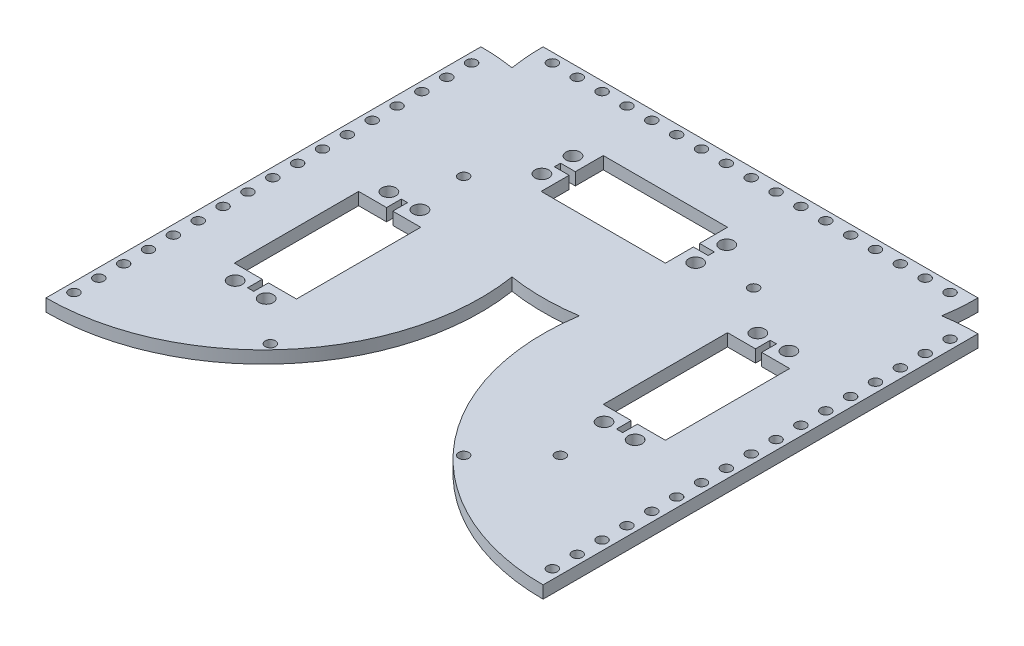
SolidWorks part; units mm, degrees
ref_plane "前视基准面" through (0, 0, 0) normal (0, 0, 1) x (1, 0, 0)
ref_plane "上视基准面" through (0, 0, 0) normal (0, 1, 0) x (1, 0, 0)
ref_plane "右视基准面" through (0, 0, 0) normal (1, 0, 0) x (0, 0, -1)
sketch "草图1" plane through (0, 0, 0) normal (0, 1, 0) x (1, 0, 0)
  line L0 (-50, 0) -> (50, 0)
  arc A0 (50, 0) -> (-50, 0) centre (0, 0) cw
extrude "凸台-拉伸1" add sketch "草图1" along normal blind 4
sketch "草图2" plane through (0, 4, 0) normal (0, 1, 0) x (1, 0, 0)
  line L2 (0, -10.623) -> (10, -10.623)
  line L3 (10, -10.623) -> (10, -30.623)
  line L4 (10, -30.623) -> (-30, -30.623)
  line L5 (-30, -30.623) -> (-30, -10.623)
  line L6 (-30, -10.623) -> (0, -10.623)
extrude "切除-拉伸1" cut sketch "草图2" against normal blind 10
sketch "草图3" plane through (0, 4, 0) normal (0, 1, 0) x (1, 0, 0)
  circle A0 centre (-34.75, -15.623) radius 2.25
  circle A1 centre (-34.75, -25.623) radius 2.25
  circle A2 centre (14.75, -25.623) radius 2.25
  circle A3 centre (14.75, -15.623) radius 2.25
extrude "切除-拉伸2" cut sketch "草图3" against normal blind 10
sketch "草图4" plane through (0, 4, 0) normal (0, 1, 0) x (1, 0, 0)
  circle A0 centre (0, -3) radius 1.65
  circle A1 centre (8, -3) radius 1.65
  circle A2 centre (16, -3) radius 1.65
  circle A3 centre (24, -3) radius 1.65
  circle A4 centre (32, -3) radius 1.65
  circle A5 centre (40, -3) radius 1.65
  circle A6 centre (-40, -3) radius 1.65
  circle A7 centre (-32, -3) radius 1.65
  circle A8 centre (-24, -3) radius 1.65
  circle A9 centre (-16, -3) radius 1.65
  circle A10 centre (-8, -3) radius 1.65
extrude "切除-拉伸3" cut sketch "草图4" against normal blind 10
sketch "草图5" plane through (0, 4, 0) normal (0, 1, 0) x (1, 0, 0)
  line L0 (-70, 0) -> (70, 0)
  circle A0 centre (0, 0) radius 70
  circle A1 centre (0, 0) radius 50
  arc M20 (-50, 0) -> (50, 0) centre (0, 0) ccw
extrude "凸台-拉伸2" add sketch "草图5" against normal blind 4 contours L0 A0 M20
sketch "草图6" plane through (0, 4, 0) normal (0, 1, 0) x (1, 0, 0)
  circle A0 centre (0, -3) radius 1.65
  circle A1 centre (8, -3) radius 1.65
  circle A2 centre (16, -3) radius 1.65
  circle A3 centre (24, -3) radius 1.65
  circle A4 centre (32, -3) radius 1.65
  circle A5 centre (40, -3) radius 1.65
  circle A6 centre (48, -3) radius 1.65
  circle A7 centre (56, -3) radius 1.65
  circle A8 centre (64, -3) radius 1.65
  circle A9 centre (-8, -3) radius 1.65
  circle A10 centre (-16, -3) radius 1.65
  circle A11 centre (-24, -3) radius 1.65
  circle A12 centre (-32, -3) radius 1.65
  circle A13 centre (-40, -3) radius 1.65
  circle A14 centre (-48, -3) radius 1.65
  circle A15 centre (-56, -3) radius 1.65
  circle A16 centre (-64, -3) radius 1.65
  dimension "D1" = 9
  dimension "D2" = 8
extrude "切除-拉伸4" cut sketch "草图6" against normal blind 4
sketch "草图7" plane through (0, 4, 0) normal (0, 1, 0) x (1, 0, 0)
  line L1 (-30, -20.623) -> (-30, -30.623)
  line L2 (10, -20.623) -> (10, -30.623)
  line L3 (-30, -30.623) -> (10, -30.623)
  line L4 (-30, -10.623) -> (-30, -30.623) construction
  line L5 (10, -30.623) -> (10, -10.623) construction
  line L7 (-30, -20.623) -> (10, -20.623)
  line L8 (-30, -20.623) -> (-30, -40.623)
  line L9 (10, -20.623) -> (10, -40.623)
  line L10 (-30, -40.623) -> (10, -40.623)
  line L11 (-34.75, -15.623) -> (14.75, -15.623)
  line L12 (14.75, -15.623) -> (14.75, -25.623)
  line L13 (14.75, -25.623) -> (14.75, -35.623)
  line L14 (-34.75, -15.623) -> (-34.75, -25.623)
  line L15 (-34.75, -25.623) -> (-34.75, -35.623)
  circle A1 centre (-34.75, -35.623) radius 2.25
  circle A2 centre (14.75, -35.623) radius 2.25
extrude "切除-拉伸5" cut sketch "草图7" against normal blind 4
sketch "草图8" plane through (0, 4, 0) normal (0, 1, 0) x (1, 0, 0)
  line L0 (-34.75, -15.623) -> (14.75, -15.623)
  line L1 (14.75, -15.623) -> (14.75, -25.623)
  line L2 (14.75, -25.623) -> (14.75, -20.623)
  line L3 (14.75, -20.623) -> (-41.5549, -20.623)
  line L4 (-41.5549, -20.623) -> (-41.5549, -8.5064)
  line L5 (-41.5549, -8.5064) -> (21.0409, -8.9873)
  line L6 (21.0409, -8.9873) -> (21.0409, -20.623)
  line L7 (21.0409, -20.623) -> (14.75, -20.623)
extrude "凸台-拉伸4" add sketch "草图8" against normal blind 4
sketch "草图9" plane through (0, 4, 0) normal (0, 1, 0) x (1, 0, 0)
  line L0 (0, -70) -> (0, -80)
  line L1 (0, -80) -> (-10, -80)
  line L2 (-10, -80) -> (10, -80)
  line L3 (80, -80) -> (77, -80)
  line L4 (80, -10) -> (80, -150)
  line L5 (-30, -20.623) -> (10, -20.623)
  line L6 (-30, -20.623) -> (-30, -40.623)
  line L7 (10, -20.623) -> (10, -40.623)
  line L8 (-30, -40.623) -> (10, -40.623)
  line L9 (59.377, -90) -> (39.377, -90)
  line L10 (59.377, -50) -> (59.377, -90)
  line L11 (59.377, -50) -> (39.377, -50)
  line L12 (39.377, -50) -> (39.377, -90)
  line L17 (-59.377, -70) -> (-39.377, -70)
  line L18 (-59.377, -110) -> (-59.377, -70)
  line L19 (-59.377, -110) -> (-39.377, -110)
  line L20 (-39.377, -110) -> (-39.377, -70)
  line L21 (-80, -10) -> (-80, -150)
  arc A1 (80, -10) -> (80, -150) centre (80, -80) ccw
  circle A2 centre (77, -80) radius 1.65
  circle A3 centre (77, -72) radius 1.65
  circle A4 centre (77, -64) radius 1.65
  circle A5 centre (77, -56) radius 1.65
  circle A6 centre (77, -48) radius 1.65
  circle A7 centre (77, -40) radius 1.65
  circle A8 centre (77, -32) radius 1.65
  circle A9 centre (77, -24) radius 1.65
  circle A10 centre (77, -16) radius 1.65
  circle A11 centre (77, -88) radius 1.65
  circle A12 centre (77, -96) radius 1.65
  circle A13 centre (77, -104) radius 1.65
  circle A14 centre (77, -112) radius 1.65
  circle A15 centre (77, -120) radius 1.65
  circle A16 centre (77, -128) radius 1.65
  circle A17 centre (77, -136) radius 1.65
  circle A18 centre (77, -144) radius 1.65
  circle A19 centre (14.75, -25.623) radius 2.25
  circle A20 centre (14.75, -35.623) radius 2.25
  circle A21 centre (-34.75, -25.623) radius 2.25
  circle A22 centre (-34.75, -35.623) radius 2.25
  circle A23 centre (44.377, -45.25) radius 2.25
  circle A24 centre (54.377, -45.25) radius 2.25
  circle A25 centre (54.377, -94.75) radius 2.25
  circle A26 centre (44.377, -94.75) radius 2.25
  circle A31 centre (-44.377, -114.75) radius 2.25
  circle A32 centre (-54.377, -114.75) radius 2.25
  circle A33 centre (-54.377, -65.25) radius 2.25
  circle A34 centre (-44.377, -65.25) radius 2.25
  circle A35 centre (-77, -144) radius 1.65
  circle A36 centre (-77, -136) radius 1.65
  circle A37 centre (-77, -128) radius 1.65
  circle A38 centre (-77, -120) radius 1.65
  circle A39 centre (-77, -112) radius 1.65
  circle A40 centre (-77, -104) radius 1.65
  circle A41 centre (-77, -96) radius 1.65
  circle A42 centre (-77, -88) radius 1.65
  circle A43 centre (-77, -80) radius 1.65
  circle A44 centre (-77, -72) radius 1.65
  circle A45 centre (-77, -64) radius 1.65
  circle A46 centre (-77, -56) radius 1.65
  circle A47 centre (-77, -48) radius 1.65
  circle A48 centre (-77, -40) radius 1.65
  circle A49 centre (-77, -32) radius 1.65
  circle A50 centre (-77, -24) radius 1.65
  circle A51 centre (-77, -16) radius 1.65
  arc A52 (-80, -10) -> (-80, -150) centre (-80, -80) cw
  point P100 (0, -80)
extrude "凸台-拉伸7" add sketch "草图9" against normal blind 4
sketch "草图10" plane through (0, 4, 0) normal (0, 1, 0) x (1, 0, 0)
  line L0 (59.377, -50) -> (59.377, -90)
  line L1 (59.377, -50) -> (39.377, -50)
  line L2 (59.377, -90) -> (39.377, -90)
  line L3 (39.377, -50) -> (39.377, -90)
  circle A0 centre (54.377, -45.25) radius 2.25
  circle A1 centre (44.377, -45.25) radius 2.25
extrude "切除-拉伸6" cut sketch "草图10" against normal blind 4
sketch "草图11" plane through (0, 0, 0) normal (0, -1, 0) x (1, 0, 0)
  line L22 (14.75, 31.623) -> (14.75, 29.623)
  line L24 (14.75, 31.623) -> (10, 31.623)
  line L25 (10, 31.623) -> (10, 29.623)
  line L26 (10, 29.623) -> (14.75, 29.623)
  line L28 (10, 31.623) -> (10, 29.623)
  line L29 (-48.377, 65.25) -> (-50.377, 65.25)
  line L32 (-30, 29.623) -> (-34.75, 29.623)
  line L33 (-30, 31.623) -> (-30, 29.623)
  line L34 (-30, 31.623) -> (-30, 29.623)
  line L35 (-34.75, 31.623) -> (-30, 31.623)
  line L36 (-34.75, 31.623) -> (-34.75, 29.623)
  line L37 (-48.377, 65.25) -> (-48.377, 70)
  line L38 (-48.377, 70) -> (-50.377, 70)
  line L39 (-50.377, 70) -> (-50.377, 65.25)
  line L40 (-48.377, 70) -> (-50.377, 70)
  line L41 (-50.377, 110) -> (-50.377, 114.75)
  line L42 (-48.377, 110) -> (-50.377, 110)
  line L43 (-48.377, 110) -> (-50.377, 110)
  line L44 (-48.377, 114.75) -> (-48.377, 110)
  line L45 (-48.377, 114.75) -> (-50.377, 114.75)
  line L56 (48.377, 94.75) -> (50.377, 94.75)
  line L57 (48.377, 94.75) -> (48.377, 90)
  line L58 (48.377, 90) -> (50.377, 90)
  line L59 (50.377, 90) -> (50.377, 94.75)
  line L60 (48.377, 90) -> (50.377, 90)
  line L61 (50.377, 50) -> (50.377, 45.25)
  line L62 (48.377, 50) -> (50.377, 50)
  line L63 (48.377, 50) -> (50.377, 50)
  line L64 (48.377, 45.25) -> (48.377, 50)
  line L65 (48.377, 45.25) -> (50.377, 45.25)
extrude "切除-拉伸9" cut sketch "草图11" against normal blind 10 contours L35 L36 L32 L33 | L25 L26 L22 L24 | L64 L65 L61 L62 | L58 L59 L56 L57 | L38 L39 L29 L37 | L44 L45 L41 L42
sketch "草图12" plane through (0, 0, 0) normal (0, -1, 0) x (1, 0, 0)
  circle A3 centre (-46.669, 48.8873) radius 1.65
  circle A6 centre (-31.1127, 126.669) radius 1.65
  circle A7 centre (31.1127, 126.669) radius 1.65
  circle A8 centre (46.669, 111.1127) radius 1.65
  circle A10 centre (31.1127, 33.331) radius 1.65
extrude "切除-拉伸10" cut sketch "草图12" against normal blind 10
